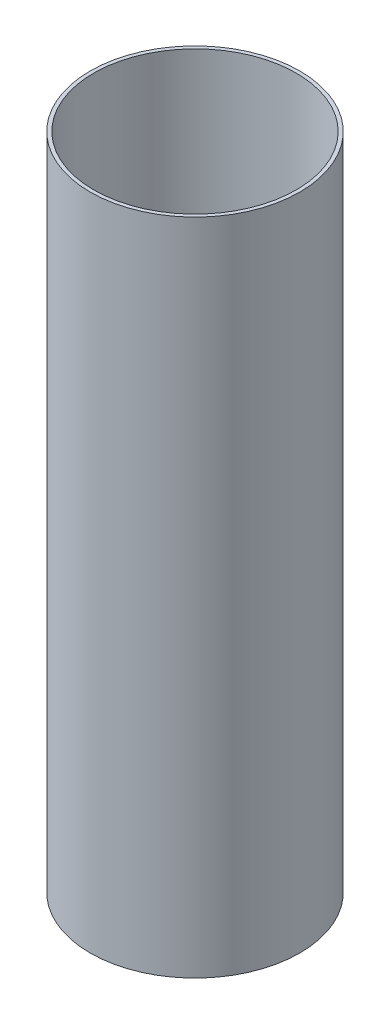
SolidWorks part; units mm, degrees
ref_plane "Front Plane" through (0, 0, 0) normal (0, 0, 1) x (1, 0, 0)
ref_plane "Top Plane" through (0, 0, 0) normal (0, 1, 0) x (1, 0, 0)
ref_plane "Right Plane" through (0, 0, 0) normal (1, 0, 0) x (0, 0, -1)
sketch "Sketch1" plane through (0, 0, 0) normal (0, 1, 0) x (1, 0, 0)
  circle A0 centre (0, 0) radius 16.9
  circle A1 centre (0, 0) radius 17.5
  dimension "D1" = 35
  dimension "D2" = 0.6
extrude "Boss-Extrude1" add sketch "Sketch1" along normal mid plane 110
